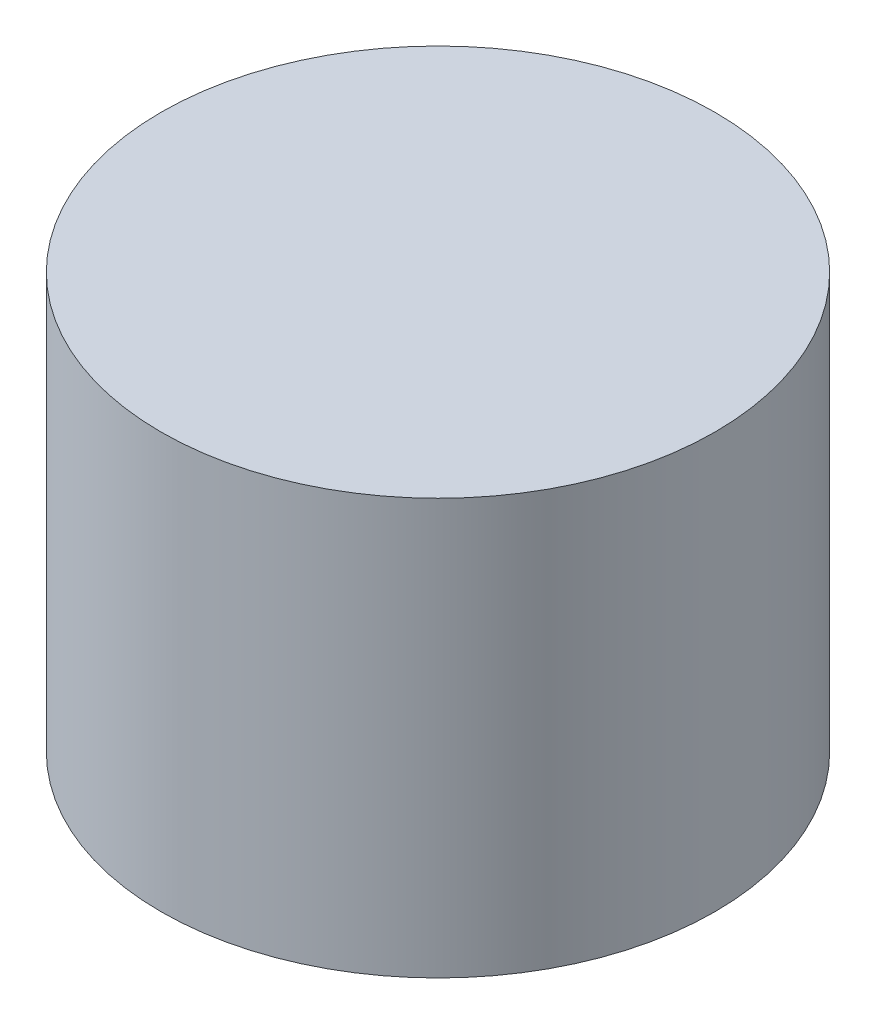
SolidWorks part; units mm, degrees
ref_plane "Front Plane" through (0, 0, 0) normal (0, 0, 1) x (1, 0, 0)
ref_plane "Top Plane" through (0, 0, 0) normal (0, 1, 0) x (1, 0, 0)
ref_plane "Right Plane" through (0, 0, 0) normal (1, 0, 0) x (0, 0, -1)
sketch "Sketch1" plane through (0, 0, 0) normal (0, 1, 0) x (1, 0, 0)
  circle A0 centre (0, 0) radius 10
extrude "Boss-Extrude1" add sketch "Sketch1" along normal blind 15 contours A0
